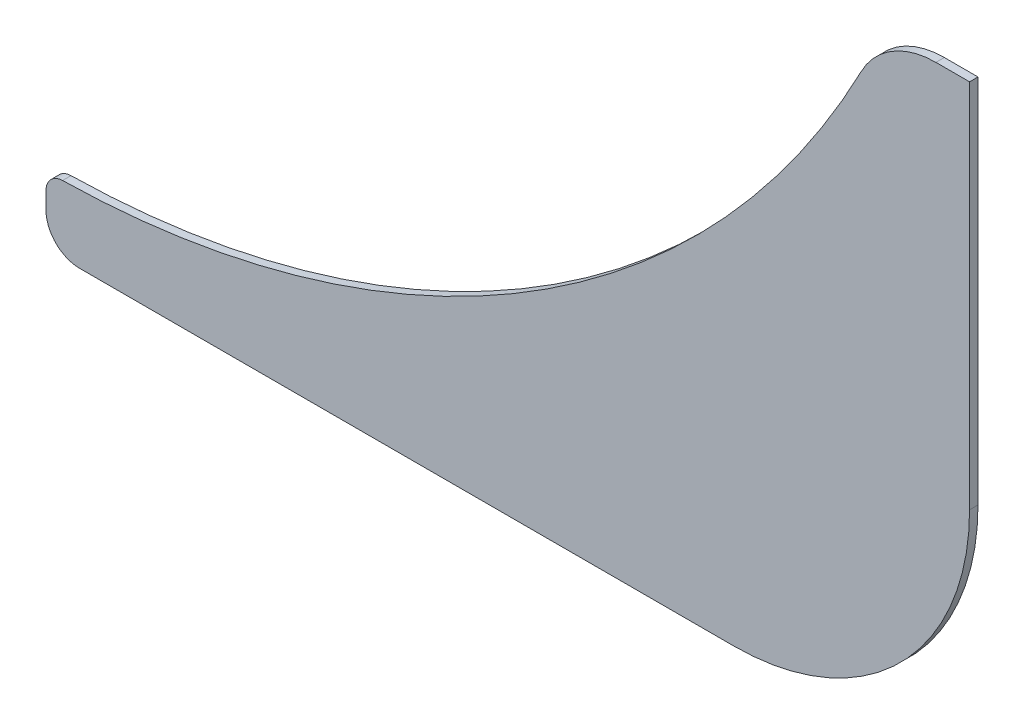
SolidWorks part; units mm, degrees
ref_plane "Front Plane" through (0, 0, 0) normal (0, 0, 1) x (1, 0, 0)
ref_plane "Top Plane" through (0, 0, 0) normal (0, 1, 0) x (1, 0, 0)
ref_plane "Right Plane" through (0, 0, 0) normal (1, 0, 0) x (0, 0, -1)
sketch "Sketch1" plane through (0, 0, 0) normal (0, 0, 1) x (1, 0, 0)
  line L15 (771.9038, 126.6023) -> (771.9038, 164.7023)
  line L17 (-107.95, -236.22) -> (-107.95, -261.62)
  line L20 (0, 0) -> (82.8917, 0) construction
  line L21 (-107.95, -236.22) -> (-282.5077, -236.22) construction
  line L22 (771.9038, 126.6023) -> (907.5478, 126.6023) construction
  line L25 (588.2488, -109.22) -> (588.2488, 170.18)
  line L26 (-82.55, -287.02) -> (410.4488, -287.02)
  line L27 (312.4515, -206.6231) -> (466.4308, -117.7231) construction
  line L28 (443.2209, -118.9957) -> (537.4488, -33.8481) construction
  line L29 (588.2488, 170.18) -> (562.8488, 170.18)
  line L40 (361.6164, -231.6548) -> (133.988, -252.7091) construction
  line L41 (157.3315, -273.5734) -> (-70.4948, -254.7805) construction
  arc A5 (-107.95, -261.62) -> (-82.55, -287.02) centre (-82.55, -261.62) ccw
  arc A6 (-107.95, -236.22) -> (506.5653, 136.0809) centre (-107.95, 457.0861) ccw
  arc A7 (588.2488, -109.22) -> (410.4488, -287.02) centre (410.4488, -109.22) cw
  arc A8 (562.8488, 170.18) -> (506.5653, 136.0809) centre (562.8488, 106.68) ccw
  spline S1 degree 3 poles (155.9851, -273.8364) (157.6707, -273.5362) (155.9614, -273.6091) (154.545, -273.5632) (151.109, -273.588) (146.869, -273.5671) (141.3082, -273.5292) (134.7264, -273.4415) (127.1182, -273.2946) (118.6055, -273.0609) (109.2803, -272.7261) (99.2556, -272.2668) (88.6466, -271.6729) (77.573, -270.9316) (66.1571, -270.0445) (54.5244, -269.0143) (42.7988, -267.8665) (31.1129, -266.6039) (19.6424, -265.3305) (8.5257, -263.8763) (-2.1301, -262.2171) (-12.2969, -260.4475) (-21.892, -258.6332) (-30.8295, -256.8671) (-39.0349, -255.237) (-46.4259, -253.8191) (-52.9324, -252.6861) (-58.4856, -251.9178) (-63.0313, -251.5394) (-66.5319, -251.6451) (-69.0472, -252.1302) (-70.6657, -253.5459) (-70.4472, -255.6917) (-68.9062, -257.778) (-66.3025, -260.229) (-62.4745, -262.9527) (-57.4718, -265.9263) (-51.2992, -269.0205) (-44.0206, -272.1448) (-35.7023, -275.171) (-26.4373, -277.9912) (-16.3291, -280.4924) (-5.4995, -282.5807) (5.9153, -284.1891) (17.7142, -285.2159) (29.7294, -285.7521) (41.8149, -286.0007) (53.9003, -285.9233) (65.8505, -285.5546) (77.5302, -284.9222) (88.8084, -284.06) (99.5605, -283.0113) (109.6699, -281.8268) (119.0235, -280.5542) (127.5233, -279.2575) (135.0819, -277.9817) (141.5945, -276.7938) (147.0755, -275.7324) (151.2398, -274.8709) (154.6131, -274.1873) (155.9851, -273.8364) (157.6707, -273.5362) (155.9614, -273.6091) knots -0.012273 -0.005484 -0.001375 0 0.001366 0.005489 0.012269 0.02165 0.033497 0.04769 0.06403 0.082338 0.102396 0.123959 0.146791 0.170641 0.19524 0.220332 0.245646 0.27091 0.295825 0.31977 0.342911 0.365083 0.386049 0.405629 0.423597 0.43978 0.453966 0.466008 0.475784 0.483219 0.48846 0.492078 0.495706 0.500976 0.508553 0.518608 0.53108 0.545907 0.56292 0.581928 0.60273 0.625094 0.648778 0.673537 0.699099 0.724814 0.750772 0.776731 0.802428 0.827555 0.851851 0.875071 0.896936 0.917223 0.935694 0.952169 0.966419 0.978318 0.987727 0.994516 0.998625 1 1.001366 1.005489 1.012269 only from (157.3315, -273.5734) to (157.3315, -273.5734) construction
  spline S3 degree 3 poles (360.3362, -232.1476) (361.944, -231.5594) (360.2733, -231.9279) (358.8705, -232.1286) (355.491, -232.7497) (351.3118, -233.4654) (345.8288, -234.3937) (339.3319, -235.4503) (331.8137, -236.6267) (323.3898, -237.8749) (314.1481, -239.1645) (304.196, -240.4529) (293.645, -241.7102) (282.6109, -242.9031) (271.2144, -244.0118) (259.5796, -245.0173) (247.8327, -245.923) (236.1052, -246.7089) (224.5878, -247.4466) (213.3874, -247.9449) (202.6055, -248.1613) (192.2857, -248.184) (182.5214, -248.0635) (173.413, -247.8762) (165.0492, -247.6957) (157.5243, -247.5827) (150.9198, -247.5968) (145.3176, -247.8045) (140.7752, -248.2212) (137.3462, -248.9332) (134.9534, -249.8477) (133.6053, -251.5229) (134.1931, -253.5982) (136.0729, -255.3852) (139.0627, -257.3468) (143.3055, -259.3644) (148.7486, -261.4241) (155.3647, -263.3995) (163.0752, -265.2124) (171.7927, -266.7481) (181.4066, -267.9166) (191.7956, -268.6246) (202.8233, -268.8006) (214.344, -268.4024) (226.142, -267.3648) (238.0677, -265.8064) (250.0128, -263.9526) (261.9011, -261.7778) (273.6057, -259.3395) (284.9982, -256.6886) (295.9553, -253.8811) (306.362, -250.9812) (316.1121, -248.0592) (325.1026, -245.1817) (333.2481, -242.4287) (340.4703, -239.8598) (346.6777, -237.559) (351.8912, -235.562) (355.8426, -233.9905) (359.046, -232.7314) (360.3362, -232.1476) (361.944, -231.5594) (360.2733, -231.9279) knots -0.012273 -0.005484 -0.001375 0 0.001366 0.005489 0.012269 0.02165 0.033497 0.04769 0.06403 0.082338 0.102396 0.123959 0.146791 0.170641 0.19524 0.220332 0.245646 0.27091 0.295825 0.31977 0.342911 0.365083 0.386049 0.405629 0.423597 0.43978 0.453966 0.466008 0.475784 0.483219 0.48846 0.492078 0.495706 0.500976 0.508553 0.518608 0.53108 0.545907 0.56292 0.581928 0.60273 0.625094 0.648778 0.673537 0.699099 0.724814 0.750772 0.776731 0.802428 0.827555 0.851851 0.875071 0.896936 0.917223 0.935694 0.952169 0.966419 0.978318 0.987727 0.994516 0.998625 1 1.001366 1.005489 1.012269 only from (361.6164, -231.6548) to (361.6164, -231.6548) construction
  spline S8 degree 3 poles (155.9851, -273.8364) (157.6707, -273.5362) (155.9614, -273.6091) (154.545, -273.5632) (151.109, -273.588) (146.869, -273.5671) (141.3082, -273.5292) (134.7264, -273.4415) (127.1182, -273.2946) (118.6055, -273.0609) (109.2803, -272.7261) (99.2556, -272.2668) (88.6466, -271.6729) (77.573, -270.9316) (66.1571, -270.0445) (54.5244, -269.0143) (42.7988, -267.8665) (31.1129, -266.6039) (19.6424, -265.3305) (8.5257, -263.8763) (-2.1301, -262.2171) (-12.2969, -260.4475) (-21.892, -258.6332) (-30.8295, -256.8671) (-39.0349, -255.237) (-46.4259, -253.8191) (-52.9324, -252.6861) (-58.4856, -251.9178) (-63.0313, -251.5394) (-66.5319, -251.6451) (-69.0472, -252.1302) (-70.6657, -253.5459) (-70.4472, -255.6917) (-68.9062, -257.778) (-66.3025, -260.229) (-62.4745, -262.9527) (-57.4718, -265.9263) (-51.2992, -269.0205) (-44.0206, -272.1448) (-35.7023, -275.171) (-26.4373, -277.9912) (-16.3291, -280.4924) (-5.4995, -282.5807) (5.9153, -284.1891) (17.7142, -285.2159) (29.7294, -285.7521) (41.8149, -286.0007) (53.9003, -285.9233) (65.8505, -285.5546) (77.5302, -284.9222) (88.8084, -284.06) (99.5605, -283.0113) (109.6699, -281.8268) (119.0235, -280.5542) (127.5233, -279.2575) (135.0819, -277.9817) (141.5945, -276.7938) (147.0755, -275.7324) (151.2398, -274.8709) (154.6131, -274.1873) (155.9851, -273.8364) (157.6707, -273.5362) (155.9614, -273.6091) knots -0.012273 -0.005484 -0.001375 0 0.001366 0.005489 0.012269 0.02165 0.033497 0.04769 0.06403 0.082338 0.102396 0.123959 0.146791 0.170641 0.19524 0.220332 0.245646 0.27091 0.295825 0.31977 0.342911 0.365083 0.386049 0.405629 0.423597 0.43978 0.453966 0.466008 0.475784 0.483219 0.48846 0.492078 0.495706 0.500976 0.508553 0.518608 0.53108 0.545907 0.56292 0.581928 0.60273 0.625094 0.648778 0.673537 0.699099 0.724814 0.750772 0.776731 0.802428 0.827555 0.851851 0.875071 0.896936 0.917223 0.935694 0.952169 0.966419 0.978318 0.987727 0.994516 0.998625 1 1.001366 1.005489 1.012269 only from (157.3315, -273.5734) to (157.3315, -273.5734) construction
  point P7 (542.5128, 119.38)
  point P19 (588.2488, -287.02)
  point P39 (157.3315, -273.5734)
  dimension "D2" = 50.8
  dimension "D3" = 25.4
  dimension "D6" = 127
  dimension "D10" = 177.8
  dimension "D11" = 63.5
  dimension "D12" = 588.2488
  dimension "D13" = 38.1
  dimension "D14" = 25.4
  dimension "D4" = 457.2
  dimension "D5" = 287.02
  dimension "D7" = 177.8
  dimension "D8" = 107.95
  dimension "D9" = 25.4
extrude "Boss-Extrude1" add sketch "Sketch1" along normal blind 6.35
fillet "Fillet1" radius 12.7 1 edges at (-107.95, -236.22, 3.175)
